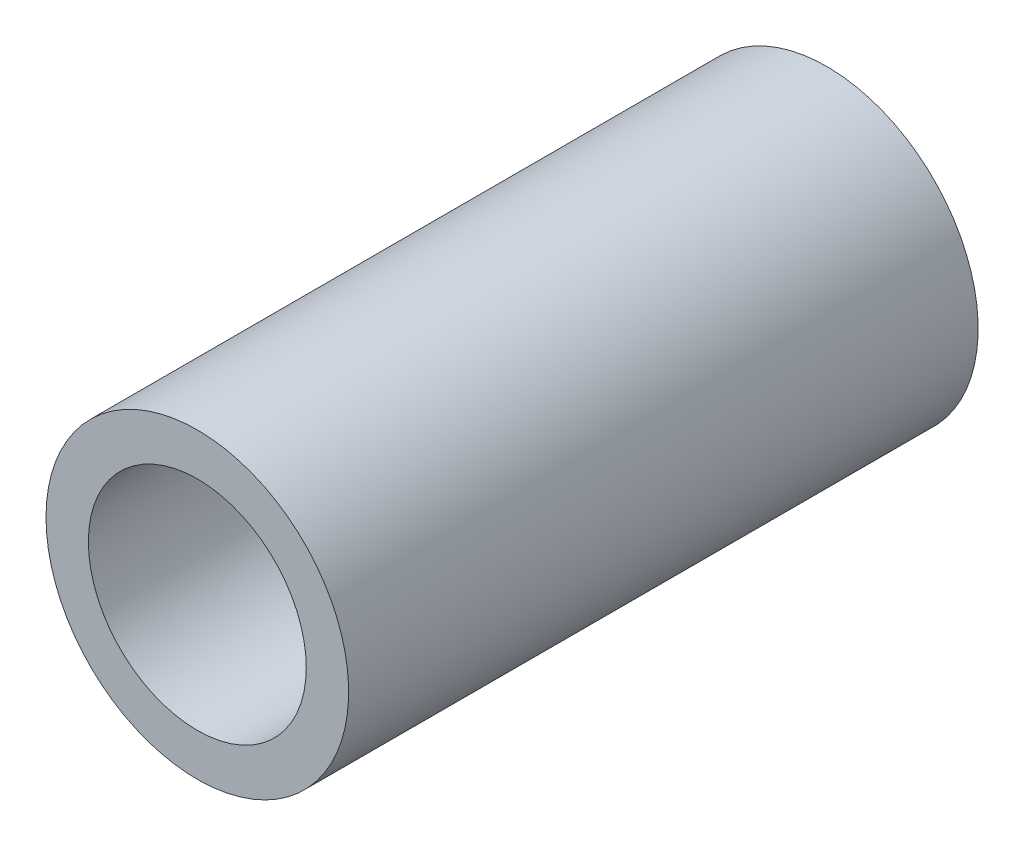
SolidWorks part; units mm, degrees
ref_plane "Piano frontale" through (0, 0, 0) normal (0, 0, 1) x (1, 0, 0)
ref_plane "Piano superiore" through (0, 0, 0) normal (0, 1, 0) x (1, 0, 0)
ref_plane "Piano destro" through (0, 0, 0) normal (1, 0, 0) x (0, 0, -1)
sketch "Schizzo1" plane through (0, 0, 0) normal (0, 0, 1) x (1, 0, 0)
  circle A0 centre (0, 0) radius 9
  circle A1 centre (0, 0) radius 12.5
  dimension "D1" = 18
  dimension "D2" = 25
extrude "Estrusione-Estrusione1" add sketch "Schizzo1" along normal mid plane 52
